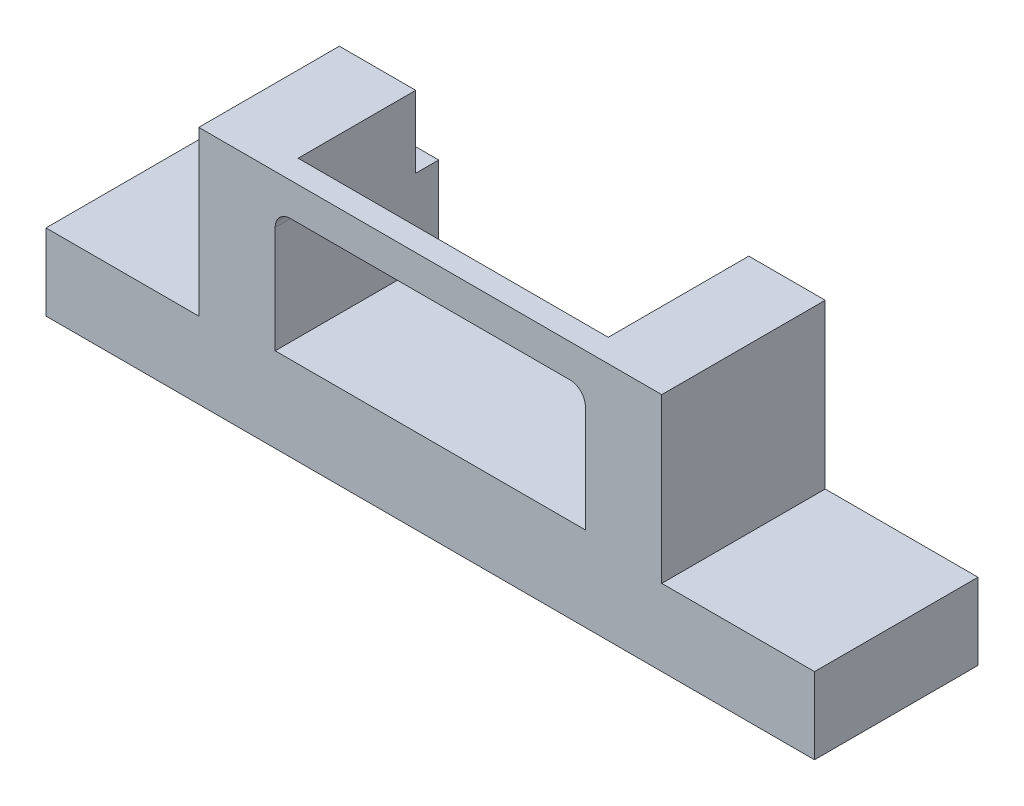
SolidWorks part; units mm, degrees
ref_plane "Alzado" through (0, 0, 0) normal (0, 0, 1) x (1, 0, 0)
ref_plane "Planta" through (0, 0, 0) normal (0, 1, 0) x (1, 0, 0)
ref_plane "Vista lateral" through (0, 0, 0) normal (1, 0, 0) x (0, 0, -1)
sketch "Croquis1" plane through (0, 0, 0) normal (0, 1, 0) x (1, 0, 0)
  line L1 (0, 0) -> (-50.3, 0)
  line L2 (0, 0) -> (0, -10.7)
  line L3 (0, -10.7) -> (-50.3, -10.7)
  line L4 (-50.3, 0) -> (-50.3, -10.7)
  dimension "D1" = 10.7
  dimension "D2" = 50.3
extrude "Saliente-Extruir1" add sketch "Croquis1" along normal blind 15.7
sketch "Croquis2" plane through (0, 0, 10.7) normal (0, 0, 1) x (1, 0, 0)
  line L0 (-50.3, 5) -> (-40.3, 5)
  line L1 (-50.3, 15.7) -> (-50.3, 0) construction
  line L2 (-40.3, 5) -> (-40.3, 15.7)
  line L3 (-50.3, 15.7) -> (0, 15.7) construction
  line L4 (-25.15, 15.7) -> (-25.15, 10.6214) construction
  line L5 (-35.3, 5.5329) -> (-15, 5.5329)
  line L6 (-34.3, 13.5329) -> (-16, 13.5329)
  line L7 (-35.3, 12.5329) -> (-35.3, 5.5329)
  line L10 (0, 5) -> (-10, 5)
  line L11 (-10, 5) -> (-10, 15.7)
  line L12 (-15, 12.5329) -> (-15, 5.5329)
  line L13 (-50.3, 5) -> (-50.3, 15.7)
  line L14 (-50.3, 15.7) -> (-40.3, 15.7)
  line L15 (0, 5) -> (0, 15.7)
  line L16 (0, 15.7) -> (-10, 15.7)
  arc A0 (-15, 12.5329) -> (-16, 13.5329) centre (-16, 12.5329) ccw
  arc A1 (-34.3, 13.5329) -> (-35.3, 12.5329) centre (-34.3, 12.5329) ccw
  point P17 (-25.15, 5.5329)
  point P18 (-25.15, 13.5329)
  point P23 (-15, 13.5329)
  point P26 (-35.3, 13.5329)
  dimension "D5" = 1
  dimension "D1" = 10
  dimension "D2" = 10.7
  dimension "D3" = 8
  dimension "D4" = 10.15
extrude "Cortar-Extruir1" cut sketch "Croquis2" against normal up to next
sketch "Croquis3" plane through (0, 15.7, 0) normal (0, 1, 0) x (1, 0, 0)
  line L0 (-40.3, -5.35) -> (-35.3, -5.35) construction
  line L1 (-40.3, 0) -> (-40.3, -10.7) construction
  line L2 (-25.15, -10.7) -> (-25.15, -9.2) construction
  line L3 (-40.3, -10.7) -> (-10, -10.7) construction
  line L4 (-10, -5.35) -> (-15, -5.35) construction
  line L5 (-10, 0) -> (-10, -10.7) construction
  line L7 (-35.3, 0) -> (-15, 0)
  line L8 (-35.3, 0) -> (-35.3, -9.2)
  line L9 (-35.3, -9.2) -> (-15, -9.2)
  line L10 (-15, 0) -> (-15, -9.2)
  dimension "D1" = 1.5
  dimension "D2" = 5
  dimension "D3" = 5
extrude "Cortar-Extruir2" cut sketch "Croquis3" against normal up to next
sketch "Croquis4" plane through (-40.3, 0, 0) normal (-1, 0, 0) x (0, 0, 1)
  line L7 (0, 15.7) -> (1.5, 15.7)
  line L8 (0, 15.7) -> (0, 11)
  line L9 (0, 11) -> (1.5, 11)
  line L10 (1.5, 15.7) -> (1.5, 11)
  dimension "D3" = 1.5
  dimension "D4" = 4.7
extrude "Cortar-Extruir3" cut sketch "Croquis4" against normal up to next
